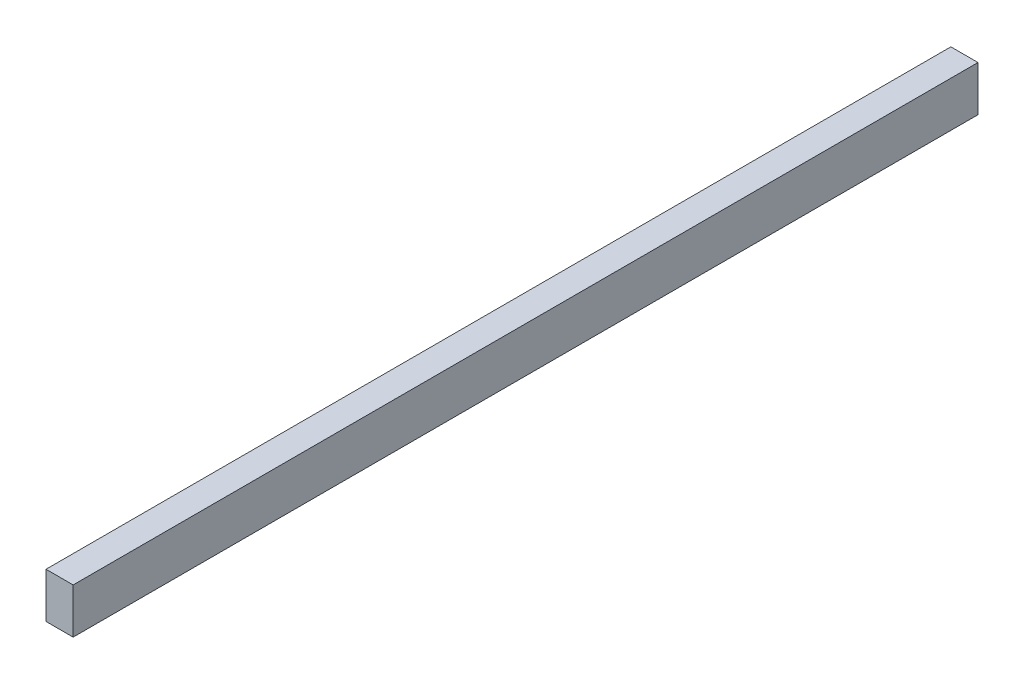
SolidWorks part; units mm, degrees
ref_plane "Płaszczyzna przednia" through (0, 0, 0) normal (0, 0, 1) x (1, 0, 0)
ref_plane "Płaszczyzna górna" through (0, 0, 0) normal (0, 1, 0) x (1, 0, 0)
ref_plane "Płaszczyzna prawa" through (0, 0, 0) normal (1, 0, 0) x (0, 0, -1)
sketch "Szkic1" plane through (0, 0, 0) normal (0, 0, 1) x (1, 0, 0)
  line L1 (-6, -10) -> (6, -10)
  line L2 (-6, -10) -> (-6, 10)
  line L3 (-6, 10) -> (6, 10)
  line L4 (6, -10) -> (6, 10)
  line L5 (0, 10) -> (0, -10) construction
  line L6 (-6, 0) -> (6, 0) construction
  point P0 (0, 0)
  dimension "D1" = 12
  dimension "D2" = 20
extrude "Dodanie-wyciągnięcie1" add sketch "Szkic1" along normal blind 400
